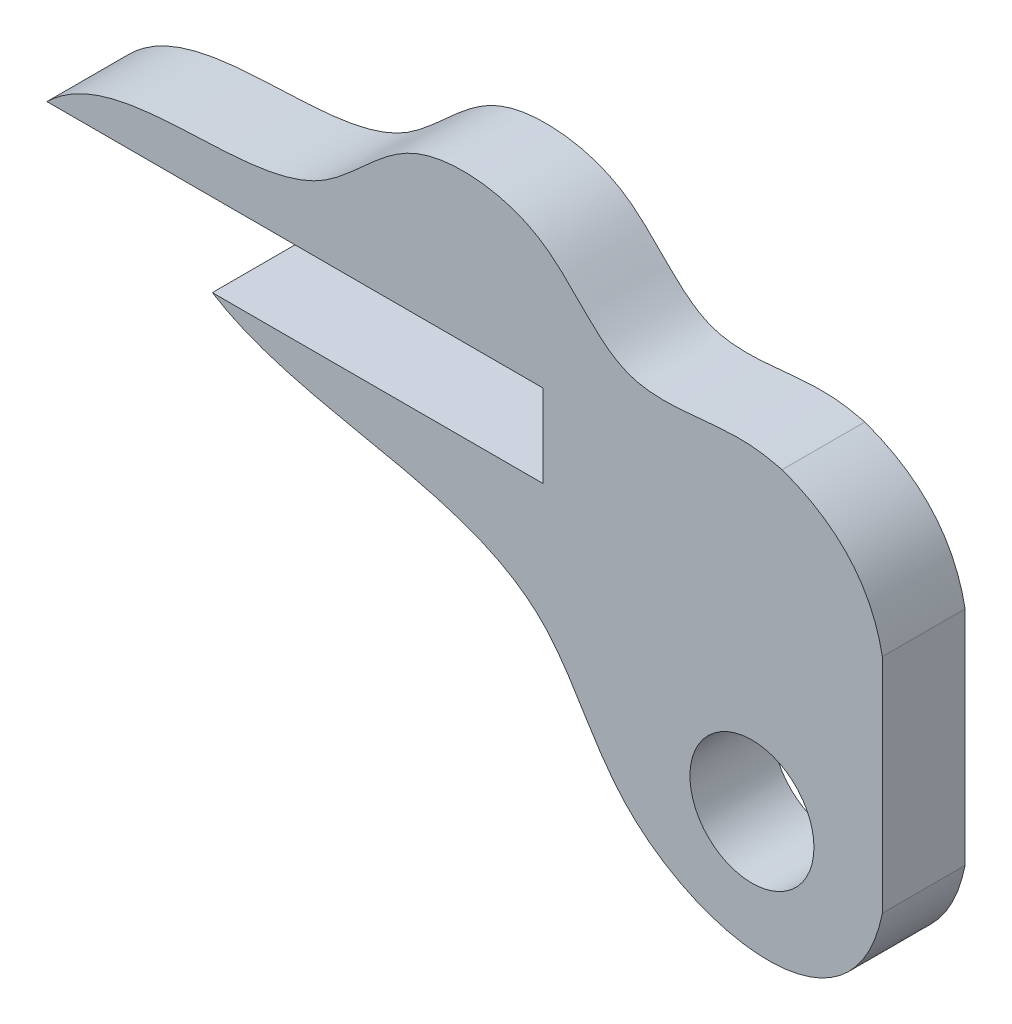
SolidWorks part; units mm, degrees
ref_plane "Front Plane" through (0, 0, 0) normal (0, 0, 1) x (1, 0, 0)
ref_plane "Top Plane" through (0, 0, 0) normal (0, 1, 0) x (1, 0, 0)
ref_plane "Right Plane" through (0, 0, 0) normal (1, 0, 0) x (0, 0, -1)
sketch "Sketch1" plane through (0, 0, 0) normal (0, 0, 1) x (1, 0, 0)
  line L0 (-76.2227, 31.8542) -> (236.8206, 31.8542) construction
  line L1 (-7.9375, 27.2355) -> (11.1125, 27.2355)
  line L2 (11.1125, 27.2355) -> (11.1125, 24.0605)
  line L3 (11.1125, 24.0605) -> (-1.5875, 24.0605)
  line L4 (24.1365, 28.4313) -> (24.1365, 16.2912)
  circle A0 centre (19.1281, 17.1644) radius 2.3813
  spline S0 degree 3 poles (-7.9375, 27.2355) (-5.1388, 29.9866) (1.482, 27.3215) (5.396, 32.7945) (8.7785, 33.0576) (11.7793, 32.0346) (14.1074, 28.2805) (19.4167, 30.095) (22.3644, 28.207) (24.1365, 28.4313) knots 0 0 0 0 0.316709 0.442153 0.523486 0.592443 0.712295 0.852347 1 1 1 1
  spline S1 degree 3 poles (-1.5875, 24.0605) (2.0188, 21.7994) (10.633, 22.7029) (14.4444, 12.3953) (23.0705, 11.0258) (24.1365, 16.2912) knots 0 0 0 0 0.438352 0.615087 1 1 1 1
  dimension "D4" = 4.7625
  dimension "D1" = 3.175
  dimension "D2" = 19.05
  dimension "D3" = 12.7
extrude "Boss-Extrude1" add sketch "Sketch1" along normal blind 3.175
sketch "Sketch2" plane through (0, 0, 3.175) normal (0, 0, 1) x (1, 0, 0)
  line L0 (24.1365, 16.2912) -> (24.1365, 28.4313) construction
  line L1 (20.2891, 29.1099) -> (24.693, 31.4424)
  line L2 (24.693, 31.4424) -> (27.7978, 27.5096)
  line L3 (27.7978, 27.5096) -> (24.1365, 24.8188)
  spline S0 degree 2 poles (24.1365, 24.8188) (23.5456, 27.9317) (20.2891, 29.1099) knots 0 0 0 1 1 1
  spline S1 degree 3 poles (24.1365, 28.4313) (22.3644, 28.207) (19.4167, 30.095) (14.1074, 28.2805) (11.7793, 32.0346) (8.7785, 33.0576) (5.396, 32.7945) (1.482, 27.3215) (-5.1388, 29.9866) (-7.9375, 27.2355) knots 0 0 0 0 0.147653 0.287705 0.407557 0.476514 0.557847 0.683291 1 1 1 1 construction
extrude "Cut-Extrude1" cut sketch "Sketch2" against normal through all
